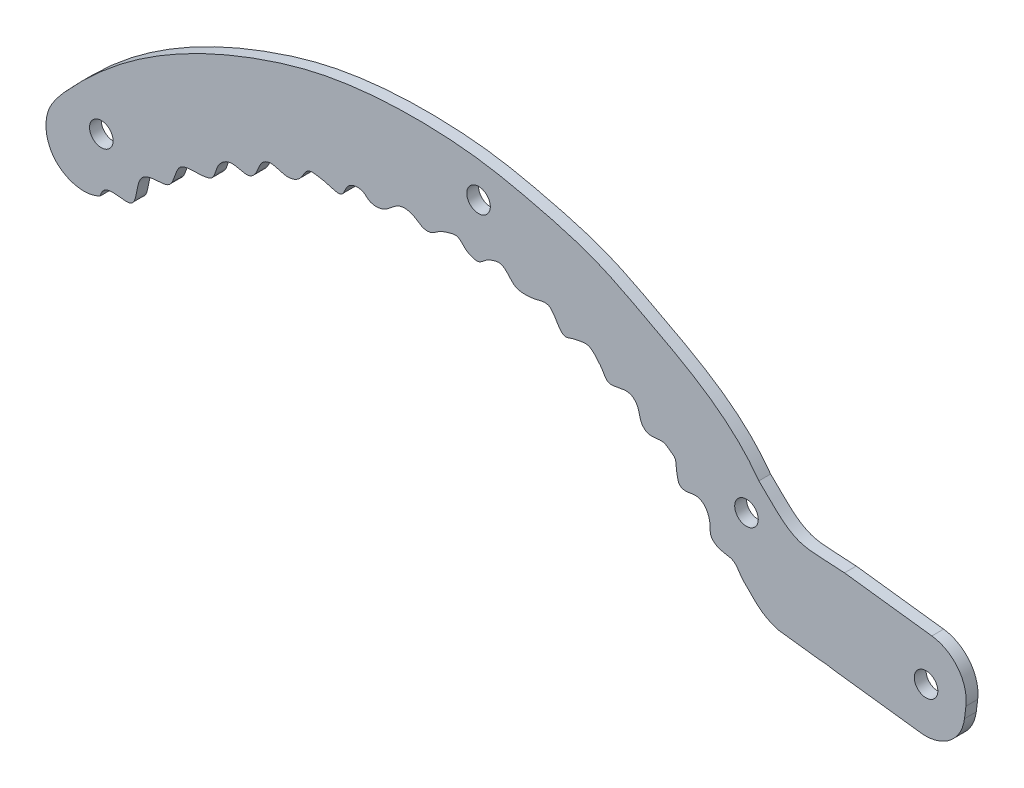
SolidWorks part; units mm, degrees
ref_plane "前视基准面" through (0, 0, 0) normal (0, 0, 1) x (1, 0, 0)
ref_plane "上视基准面" through (0, 0, 0) normal (0, 1, 0) x (1, 0, 0)
ref_plane "右视基准面" through (0, 0, 0) normal (1, 0, 0) x (0, 0, -1)
sketch "草图1" plane through (0, 0, 0) normal (0, 0, 1) x (1, 0, 0)
  line L0 (-0.5209, -5.5459) -> (-11.4028, -4.1843)
  line L1 (-13.704, -3.8964) -> (-18.7413, -3.2661)
  line L2 (-10.228, 7.2426) -> (0.905, 5.8496)
  line L3 (5.2455, 0.2675) -> (5.0612, -1.2054)
  circle A0 centre (-104.9061, 8.3116) radius 1.5
  circle A1 centre (-22.7093, 7.6342) radius 1.5
  circle A2 centre (0.1673, 0.1455) radius 1.5
  circle A3 centre (-56.8472, 25.0725) radius 1.5
  arc A4 (-0.5209, -5.5459) -> (5.0612, -1.2054) centre (0.0999, -0.5846) ccw
  arc A5 (5.2455, 0.2675) -> (0.905, 5.8496) centre (0.2842, 0.8882) ccw
  spline S0 degree 3 poles (-13.704, -3.8964) (-12.9336, -3.947) (-12.1667, -4.0215) (-11.4028, -4.1843) knots 0.407976 0.407976 0.407976 0.407976 0.440425 0.440425 0.440425 0.440425
  spline S1 degree 3 poles (-47.403, 17.376) (-47.0506, 17.1534) (-46.3424, 15.0704) (-44.9615, 15.7969) (-44.08, 15.8856) (-43.2019, 16.1634) (-42.3798, 15.7873) (-41.7087, 15.0409) (-41.0333, 14.2657) (-40.4097, 12.9401) (-38.8587, 13.359) (-37.3991, 13.5182) (-36.1933, 12.1204) (-36.3622, 10.8798) (-35.6594, 10.3528) knots 0 0 0 0 0.161236 0.212348 0.265446 0.336193 0.378688 0.430637 0.526782 0.58317 0.682557 0.781271 0.853714 1 1 1 1
  spline S2 degree 3 poles (-71.2074, 18.3754) (-70.5614, 17.671) (-68.6316, 17.7283) (-67.4144, 19.3567) (-65.8931, 19.5413) (-64.8299, 19.078) (-63.9005, 18.3417) (-62.7356, 18.3763) (-61.9138, 19.1601) (-60.7965, 19.5094) (-59.4524, 19.948) (-58.6621, 18.8662) (-57.8015, 18.3679) (-56.7226, 18.0971) (-55.976, 18.9428) (-55.0483, 19.3272) (-53.9886, 19.6035) (-53.037, 18.7817) (-52.2572, 17.7014) (-50.7674, 17.5619) (-49.1702, 17.7658) (-47.922, 18.2641) (-47.403, 17.376) knots 0 0 0 0 0.101433 0.182304 0.213922 0.268057 0.309966 0.345938 0.38914 0.432999 0.482664 0.529097 0.56672 0.598853 0.644173 0.680167 0.715861 0.759457 0.810996 0.863338 0.916048 1 1 1 1
  spline S3 degree 3 poles (-105.0346, 1.419) (-104.5372, 3.5567) (-99.9157, 0.7261) (-100.6863, 6.3357) (-97.9919, 6.7632) (-95.612, 6.7883) (-95.5063, 10.3022) (-92.6858, 10.0411) (-90.4714, 10.3472) (-90.2857, 12.3318) (-88.7206, 13.6368) (-87.1967, 13.2015) (-85.973, 13.0037) (-84.9761, 13.9694) (-84.7929, 15.2735) (-83.2755, 16.1679) (-82.0121, 15.4734) (-80.5883, 15.4292) (-79.3284, 16.065) (-78.817, 17.6716) (-77.0777, 17.4724) (-75.8926, 17.1933) (-74.0768, 16.5834) (-73.6604, 18.8842) (-71.8275, 18.9365) (-71.2074, 18.3754) knots 0 0 0 0 0.100332 0.18604 0.234954 0.2703 0.337742 0.40192 0.43828 0.47683 0.523229 0.559517 0.584173 0.604077 0.648703 0.670042 0.71595 0.738313 0.768611 0.808998 0.834826 0.875875 0.9064 0.941714 1 1 1 1
  spline S4 degree 3 poles (-21.1308, 11.9336) (-24.8609, 17.1629) (-32.1643, 20.8937) (-42.137, 26.2166) (-49.0452, 28.0557) (-55.8035, 29.5354) (-61.9486, 30.1048) (-69.5291, 30.1083) (-77.0729, 29.0917) (-83.8843, 27.0299) (-91.4089, 24.1709) (-100.5365, 19.2605) (-107.7223, 12.8664) (-111.9642, 7.8751) (-112.0387, 4.671) (-110.3883, 1.2356) (-106.9887, 0.3608) (-105.0346, 1.419) knots 0 0 0 0 0.162309 0.214041 0.297346 0.349154 0.396315 0.45953 0.548645 0.595484 0.646703 0.76082 0.864659 0.902713 0.926128 0.944547 1 1 1 1
  spline S5 degree 3 poles (-10.228, 7.2426) (-10.9119, 7.281) (-12.8351, 7.456) (-17.158, 7.4132) (-19.6512, 10.6162) (-21.1308, 11.9336) knots 0.763962 0.763962 0.763962 0.763962 0.803221 0.875531 1 1 1 1
  spline S6 degree 3 poles (-35.6594, 10.3528) (-34.9395, 9.6917) (-33.5154, 10.5785) (-32.4687, 9.5794) (-31.7059, 9.1743) (-31.6928, 8.1202) (-31.5349, 7.2763) (-31.3113, 6.3409) (-30.3093, 6.0168) (-29.356, 6.4278) (-28.2337, 6.0594) (-27.5751, 5.1489) (-27.2848, 4.0191) (-27.4028, 2.901) (-26.7245, 2.1435) (-25.699, 1.7399) (-24.1441, 1.6968) (-23.5045, 0.3032) (-22.3179, -0.8674) (-21.1399, -2.161) (-19.6787, -2.9453) (-18.9279, -3.2079) (-18.7413, -3.2661) knots 0 0 0 0 0.036098 0.047993 0.058182 0.069735 0.087709 0.096698 0.107024 0.126401 0.138603 0.153227 0.171393 0.187122 0.197486 0.211172 0.233173 0.256561 0.268556 0.303732 0.328872 0.33707 0.33707 0.33707 0.33707
extrude "凸台-拉伸1" add sketch "草图1" along normal blind 1.5
